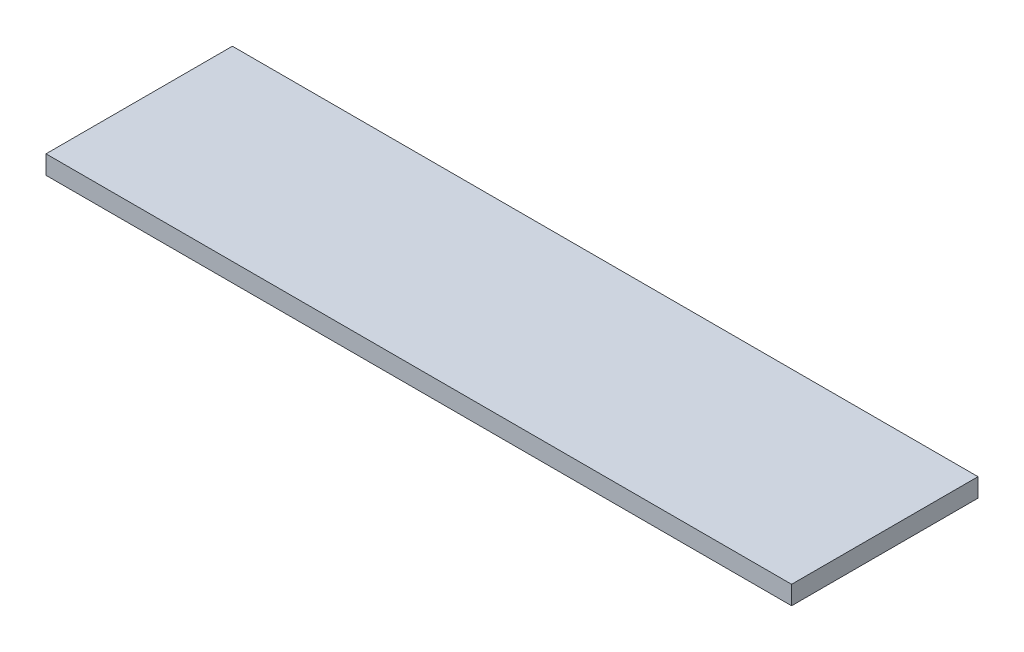
SolidWorks part; units mm, degrees
ref_plane "Front Plane" through (0, 0, 0) normal (0, 0, 1) x (1, 0, 0)
ref_plane "Top Plane" through (0, 0, 0) normal (0, 1, 0) x (1, 0, 0)
ref_plane "Right Plane" through (0, 0, 0) normal (1, 0, 0) x (0, 0, -1)
sketch "Sketch1" plane through (0, 0, 0) normal (0, 1, 0) x (1, 0, 0)
  line L1 (-200, 50) -> (200, 50)
  line L2 (-200, 50) -> (-200, -50)
  line L3 (-200, -50) -> (200, -50)
  line L4 (200, 50) -> (200, -50)
  line L5 (-200, 50) -> (200, -50) construction
  line L6 (-200, -50) -> (200, 50) construction
  point P0 (0, 0)
  dimension "D1" = 400
  dimension "D2" = 100
extrude "Boss-Extrude1" add sketch "Sketch1" along normal blind 10
